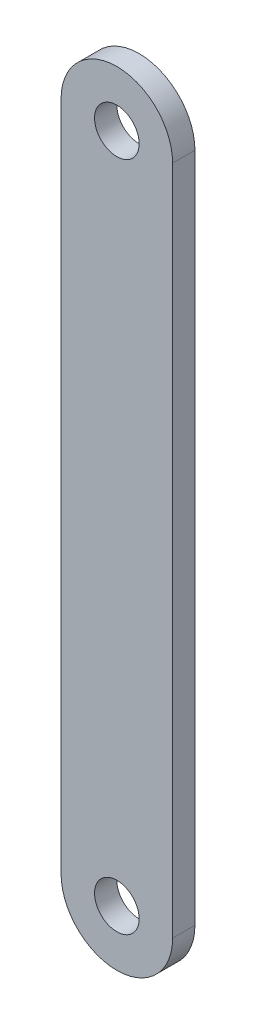
SolidWorks part; units mm, degrees
ref_plane "Alzado" through (0, 0, 0) normal (0, 0, 1) x (1, 0, 0)
ref_plane "Planta" through (0, 0, 0) normal (0, 1, 0) x (1, 0, 0)
ref_plane "Vista lateral" through (0, 0, 0) normal (1, 0, 0) x (0, 0, -1)
sketch "Croquis1" plane through (0, 0, 0) normal (0, 0, 1) x (1, 0, 0)
  line L0 (0, 0) -> (50, 0) construction
  line L1 (50, 0) -> (50, 300.9)
  line L2 (50, 300.9) -> (0, 300.9) construction
  line L3 (0, 300.9) -> (0, 0)
  arc A0 (0, 0) -> (50, 0) centre (25, 0) ccw
  arc A1 (50, 300.9) -> (0, 300.9) centre (25, 300.9) ccw
  circle A2 centre (25, 300.9) radius 10
  circle A3 centre (25, 0) radius 10
  dimension "D3" = 20
  dimension "D4" = 20
  dimension "D1" = 50
  dimension "D2" = 300.9
extrude "Saliente-Extruir1" add sketch "Croquis1" along normal blind 10
